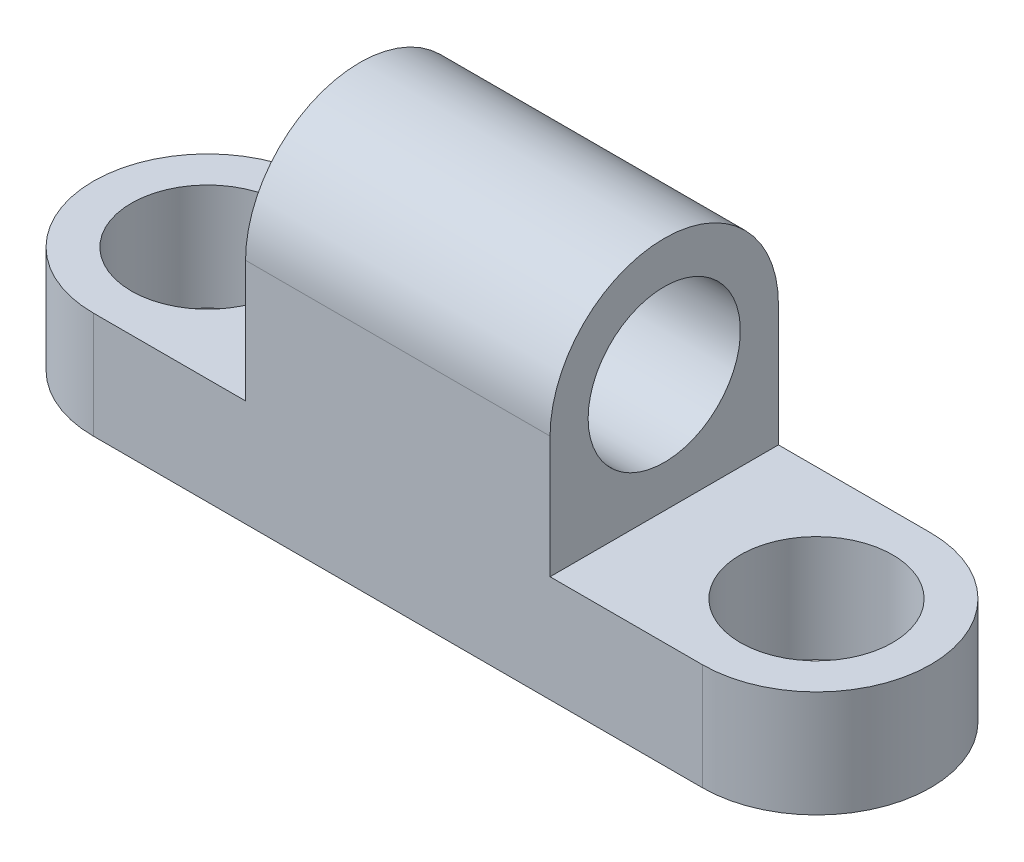
SolidWorks part; units mm, degrees
ref_plane "Front Plane" through (0, 0, 0) normal (0, 0, 1) x (1, 0, 0)
ref_plane "Top Plane" through (0, 0, 0) normal (0, 1, 0) x (1, 0, 0)
ref_plane "Right Plane" through (0, 0, 0) normal (1, 0, 0) x (0, 0, -1)
sketch "Croquis1" plane through (0, 0, 0) normal (0, 1, 0) x (1, 0, 0)
  line L0 (0, 0) -> (80, 0)
  line L2 (80, 30) -> (0, 30)
  line L4 (0, 30) -> (0, 0) construction
  line L5 (0, 30) -> (20, 30)
  line L6 (20, 30) -> (60, 30)
  line L7 (60, 30) -> (80, 30)
  line L8 (20, 30) -> (20, 0)
  line L9 (20, 0) -> (60, 0)
  line L10 (60, 0) -> (60, 30)
  arc A0 (0, 30) -> (0, 0) centre (0, 15) ccw
  arc A1 (80, 0) -> (80, 30) centre (80, 15) ccw
  circle A2 centre (0, 15) radius 10
  circle A3 centre (80, 15) radius 10
  dimension "D1" = 30
  dimension "D2" = 30
  dimension "D5" = 20
  dimension "D6" = 20
  dimension "D3" = 80
  dimension "D4" = 30
  dimension "D7" = 20
  dimension "D8" = 20
extrude "Saliente-Extruir1" add sketch "Croquis1" along normal blind 14 contours A0 L0 A1 L2
sketch "Croquis2" plane through (0, 14, 0) normal (0, 1, 0) x (1, 0, 0)
  line L1 (0, 0) -> (80, 0) construction
  line L2 (20, 0) -> (60, 0)
  line L6 (80, 30) -> (0, 30) construction
  line L7 (60, 30) -> (60, 0)
  line L8 (60, 30) -> (20, 30)
  line L9 (20, 30) -> (20, 0)
  dimension "D1" = 40
extrude "Saliente-Extruir2" add sketch "Croquis2" along normal blind 16
sketch "Croquis3" plane through (20, 0, 0) normal (-1, 0, 0) x (0, 0, 1)
  line L0 (-30, 30) -> (0, 30) construction
  circle A0 centre (-15, 30) radius 15
extrude "Saliente-Extruir4" add sketch "Croquis3" against normal blind 40 contours A0
sketch "Croquis6" plane through (20, 0, 0) normal (-1, 0, 0) x (0, 0, 1)
  line L0 (-15, 14) -> (-15, 45) construction
  line L1 (0, 14) -> (-30, 14) construction
  arc A0 (0, 30) -> (-30, 30) centre (-15, 30) ccw construction
  circle A1 centre (-15, 29.5) radius 10
  dimension "D1" = 20
extrude "Cortar-Extruir1" cut sketch "Croquis6" against normal blind 96
sketch "Croquis8" plane through (0, 14, 0) normal (0, 1, 0) x (1, 0, 0)
  line L0 (0, 30) -> (0, 0) construction
  circle A0 centre (0, 15) radius 10
  point P6 (0, 0)
  dimension "D1" = 20
extrude "Cortar-Extruir2" cut sketch "Croquis8" against normal blind 96
sketch "Croquis11" plane through (0, 14, 0) normal (0, 1, 0) x (1, 0, 0)
  circle A0 centre (80, 15) radius 10
  dimension "D1" = 20
extrude "Cortar-Extruir3" cut sketch "Croquis11" against normal blind 96
